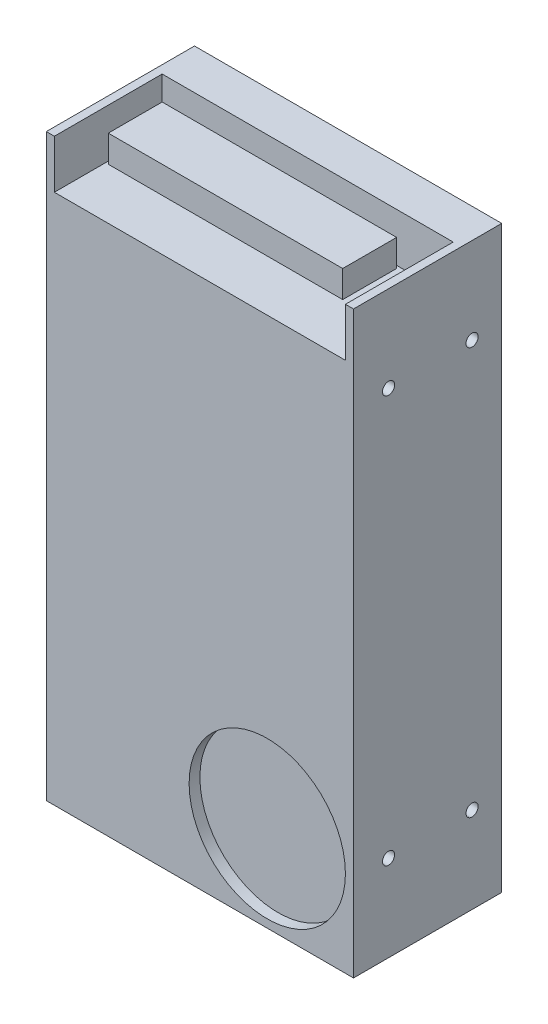
SolidWorks part; units mm, degrees
ref_plane "Front Plane" through (0, 0, 0) normal (0, 0, 1) x (1, 0, 0)
ref_plane "Top Plane" through (0, 0, 0) normal (0, 1, 0) x (1, 0, 0)
ref_plane "Right Plane" through (0, 0, 0) normal (1, 0, 0) x (0, 0, -1)
sketch "Sketch1" plane through (0, 0, 0) normal (0, 0, 1) x (1, 0, 0)
  line L1 (-57, 107.5) -> (57, 107.5)
  line L2 (-57, 107.5) -> (-57, -107.5)
  line L3 (-57, -107.5) -> (57, -107.5)
  line L4 (57, 107.5) -> (57, -107.5)
  line L5 (-57, 107.5) -> (57, -107.5) construction
  line L6 (-57, -107.5) -> (57, 107.5) construction
  point P0 (0, 0)
  dimension "D1" = 114
  dimension "D2" = 215
extrude "Boss-Extrude1" add sketch "Sketch1" along normal blind 55
sketch "Sketch2" plane through (0, 0, 55) normal (0, 0, 1) x (1, 0, 0)
  line L0 (57, 107.5) -> (-57, 107.5) construction
  line L1 (-54, 107.5) -> (54, 107.5)
  line L2 (-54, 107.5) -> (-54, 89.5)
  line L3 (-54, 89.5) -> (54, 89.5)
  line L4 (54, 107.5) -> (54, 89.5)
  line L5 (57, -107.5) -> (57, 107.5) construction
  line L6 (-57, 107.5) -> (-57, -107.5) construction
  dimension "D1" = 18
extrude "Cut-Extrude1" cut sketch "Sketch2" against normal blind 40
sketch "Sketch3" plane through (0, 89.5, 0) normal (0, 1, 0) x (1, 0, 0)
  line L0 (-54, -15) -> (-54, -55) construction
  line L1 (-53, -16) -> (34, -16)
  line L2 (-53, -16) -> (-53, -36)
  line L3 (-53, -36) -> (34, -36)
  line L4 (34, -16) -> (34, -36)
  line L5 (54, -15) -> (54, -55) construction
  line L6 (54, -15) -> (-54, -15) construction
  dimension "D1" = 1
  dimension "D2" = 20
  dimension "D3" = 1
  dimension "D4" = 20
extrude "Boss-Extrude2" add sketch "Sketch3" along normal blind 10
sketch "Sketch4" plane through (0, 0, 55) normal (0, 0, 1) x (1, 0, 0)
  line L0 (57, -107.5) -> (57, 107.5) construction
  line L1 (-57, -107.5) -> (57, -107.5) construction
  circle A0 centre (25, -75.5) radius 29
  dimension "D3" = 58
extrude "Cut-Extrude3" cut sketch "Sketch4" against normal blind 4
sketch "Sketch5" plane through (0, 0, 0) normal (0, 0, -1) x (-1, 0, 0)
  line L0 (-57, -107.5) -> (-57, 107.5) construction
  line L1 (-57, 107.5) -> (57, 107.5) construction
  circle A0 centre (-25, 75.5) radius 2.25
  circle A1 centre (25, 75.5) radius 2.25
  circle A2 centre (25, -75.5) radius 2.25
  circle A3 centre (-25, -75.5) radius 2.25
  dimension "D1" = 4.5
  dimension "D2" = 32
  dimension "D3" = 32
  dimension "D4" = 2
  dimension "D5" = 2
extrude "Cut-Extrude4" cut sketch "Sketch5" against normal blind 15
sketch "Sketch6" plane through (-57, 0, 0) normal (-1, 0, 0) x (0, 0, 1)
  line L0 (55, 107.5) -> (0, 107.5) construction
  line L1 (0, 107.5) -> (0, -107.5) construction
  line L2 (55, 107.5) -> (55, -107.5) construction
  circle A0 centre (11, 75.5) radius 2.25
  circle A1 centre (42, 75.5) radius 2.25
  circle A2 centre (42, -75.5) radius 2.25
  circle A3 centre (11, -75.5) radius 2.25
  dimension "D1" = 32
  dimension "D2" = 11
  dimension "D5" = 13
  dimension "D3" = 2
  dimension "D4" = 2
extrude "Cut-Extrude5" cut sketch "Sketch6" against normal through all
